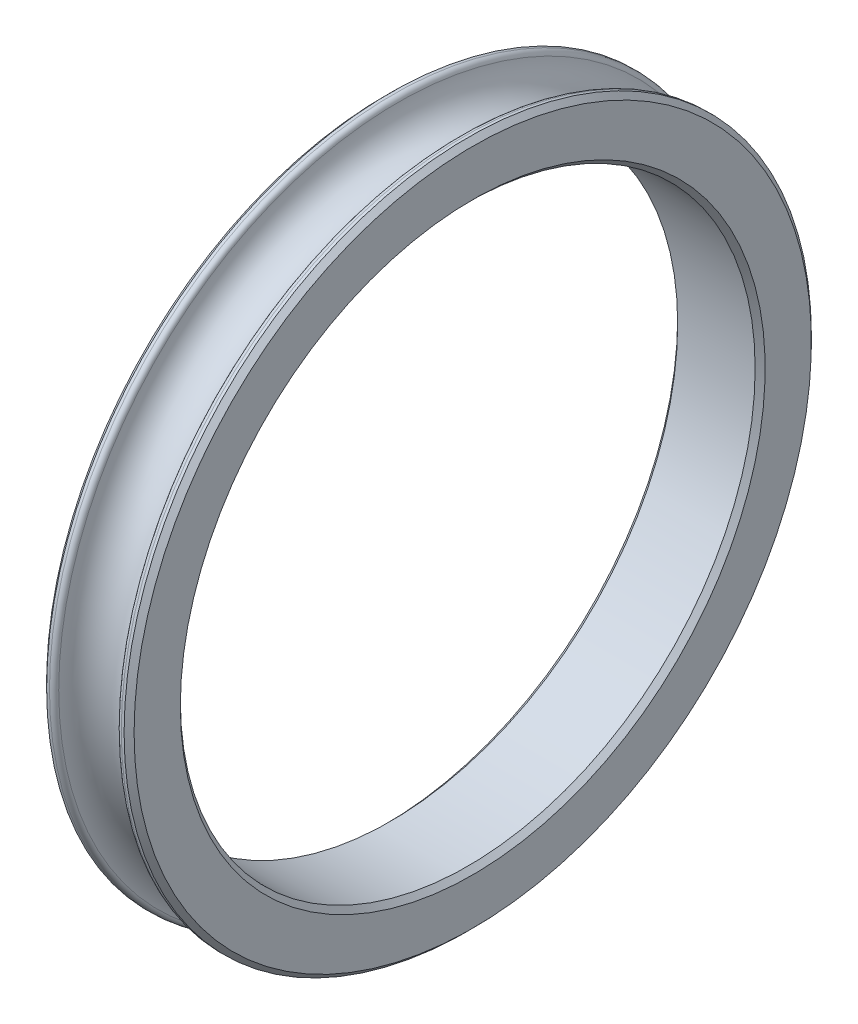
SolidWorks part; units mm, degrees
ref_plane "前视基准面" through (0, 0, 0) normal (0, 0, 1) x (1, 0, 0)
ref_plane "上视基准面" through (0, 0, 0) normal (0, 1, 0) x (1, 0, 0)
ref_plane "右视基准面" through (0, 0, 0) normal (1, 0, 0) x (0, 0, -1)
sketch "草图1" plane through (0, 0, 0) normal (0, 0, 1) x (1, 0, 0)
  line L0 (-16.5806, 0) -> (15.9821, 0) construction
  line L1 (0, 30.6673) -> (0, -24.0928) construction
  line L3 (3.5, 23) -> (0, 23)
  line L6 (2.5, 27.5) -> (3.5, 27.5)
  line L7 (3.5, 27.5) -> (3.5, 23)
  line L8 (-3.5, 23) -> (0, 23)
  line L9 (-2.5, 27.5) -> (-3.5, 27.5)
  line L10 (-3.5, 27.5) -> (-3.5, 23)
  arc A0 (-2.5, 27.5) -> (2.5, 27.5) centre (0, 27.5) ccw
  point P3 (0, 0)
  point P9 (5, 23)
  point P10 (1.75, 23)
  point P12 (5, 23)
  point P14 (5, 23)
  point P15 (-1.75, 23)
  point P17 (5, 23)
  point P18 (5.1885, 23)
  point P19 (0, 0)
  point P20 (0, 27.4842)
  point P21 (0, 0)
  dimension "D1" = 2.5
  dimension "D2" = 23
  dimension "D3" = 27.5
  dimension "D4" = 7
revolve "旋转1" add sketch "草图1" angle 360 about L0
fillet "圆角1" radius 0.4 2 edges at (2.5, 0, 27.5) (-2.5, 0, 27.5)
chamfer "倒角1" distance 0.4 angle 45 4 edges at (3.5, 0, 27.5) (3.5, 0, 23) (-3.5, 0, 27.5) (-3.5, 0, 23)
